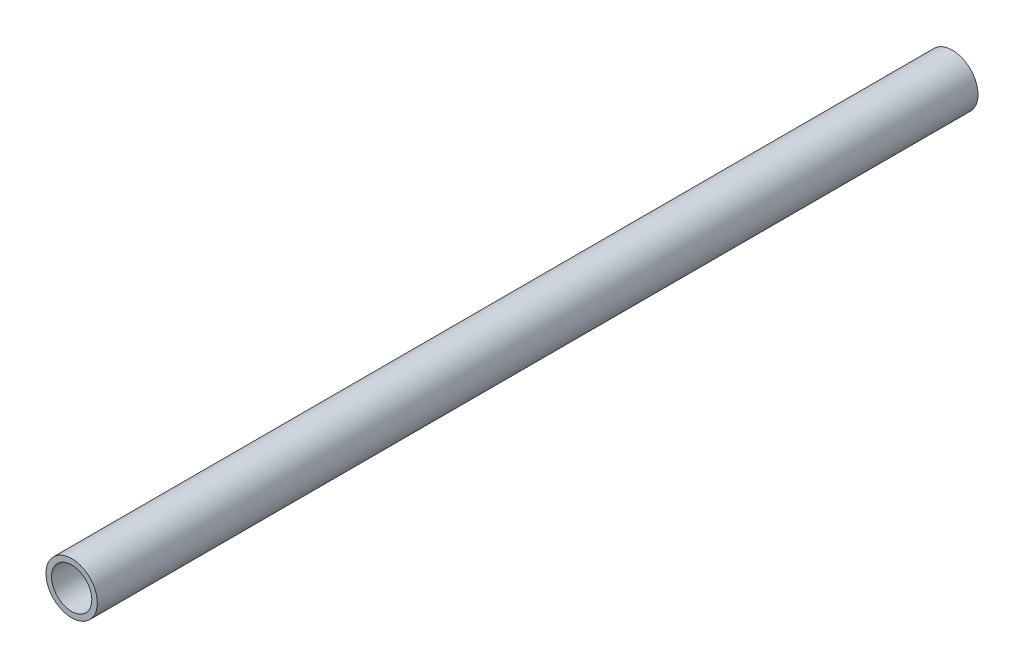
SolidWorks part; units mm, degrees
ref_plane "Front Plane" through (0, 0, 0) normal (0, 0, 1) x (1, 0, 0)
ref_plane "Top Plane" through (0, 0, 0) normal (0, 1, 0) x (1, 0, 0)
ref_plane "Right Plane" through (0, 0, 0) normal (1, 0, 0) x (0, 0, -1)
sketch "Sketch1" plane through (0, 0, 0) normal (0, 0, 1) x (1, 0, 0)
  circle A0 centre (0, 0) radius 10.4648
  circle A1 centre (0, 0) radius 13.335
  dimension "D1" = 2.8702
  dimension "D2" = 26.67
extrude "Boss-Extrude1" add sketch "Sketch1" along normal blind 457.2
